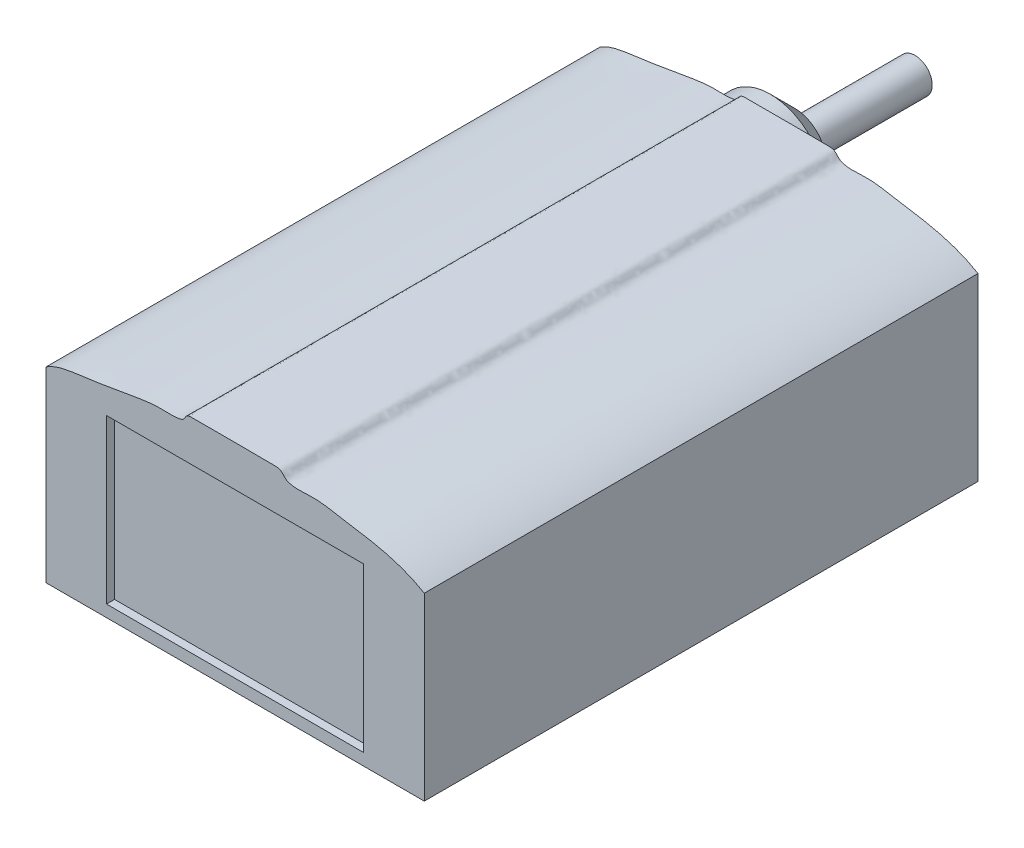
SolidWorks part; units mm, degrees
ref_plane "Спереди" through (0, 0, 0) normal (0, 0, 1) x (1, 0, 0)
ref_plane "Сверху" through (0, 0, 0) normal (0, 1, 0) x (1, 0, 0)
ref_plane "Справа" through (0, 0, 0) normal (1, 0, 0) x (0, 0, -1)
sketch "Эскиз2" plane through (0, 0, 0) normal (0, 0, 1) x (1, 0, 0)
  line L0 (-188.0475, -103.6209) -> (-140.9775, -103.6209) construction
  line L3 (-188.0519, -83.2642) -> (-188.0519, -106.5212)
  line L4 (-188.0519, -106.5212) -> (-140.9819, -106.5212)
  line L5 (-140.9819, -84.1097) -> (-140.9819, -106.5212)
  spline S0 degree 3 poles (-188.0519, -83.2642) (-186.7514, -82.4001) (-184.0147, -82.0982) (-180.2698, -81.5393) (-177.1144, -80.9668) (-174.1299, -80.4879) (-172.3112, -80.7264) (-170.781, -80.4021) (-170.711, -79.668) (-168.6764, -79.5975) (-161.9112, -79.6747) (-158.7559, -79.6611) (-158.3387, -80.4501) (-156.8599, -80.9524) (-154.6505, -80.5007) (-151.0707, -81.2671) (-146.3736, -81.8973) (-142.9268, -82.9516) (-140.9819, -84.1097) knots 0 0 0 0 0.130689 0.231656 0.325449 0.407811 0.483445 0.495515 0.524852 0.540814 0.63917 0.653662 0.671246 0.679565 0.734653 0.804528 0.874807 1 1 1 1
  dimension "D1" = 47.07
  dimension "D2" = 47.07
extrude "Бобышка-Вытянуть1" add sketch "Эскиз2" along normal blind 68.9
sketch "Эскиз3" plane through (0, 0, 0) normal (0, 0, -1) x (-1, 0, 0)
  circle A0 centre (176.6111, -94.4581) radius 6.95
  dimension "D1" = 13.9
extrude "Бобышка-Вытянуть2" add sketch "Эскиз3" along normal blind 12.8
chamfer "Фаска1" distance 3 angle 45 1 edges at (-183.5611, -94.4581, -12.8)
sketch "Эскиз4" plane through (0, 0, -12.8) normal (0, 0, -1) x (-1, 0, 0)
  circle A0 centre (176.6111, -94.4581) radius 2.1358
extrude "Бобышка-Вытянуть3" add sketch "Эскиз4" along normal blind 15
sketch "Эскиз5" plane through (0, 0, 68.9) normal (0, 0, 1) x (1, 0, 0)
  line L0 (-164.5169, -106.5212) -> (-164.5169, -76.1098) construction
  line L1 (-180.5169, -84.7327) -> (-148.5169, -84.7327)
  line L2 (-180.5169, -84.7327) -> (-180.5169, -105.0527)
  line L3 (-180.5169, -105.0527) -> (-148.5169, -105.0527)
  line L4 (-148.5169, -84.7327) -> (-148.5169, -105.0527)
  line L5 (-188.0519, -106.5212) -> (-140.9819, -106.5212) construction
  line L6 (-188.0519, -94.8927) -> (-140.9819, -94.8927) construction
  line L7 (-188.0519, -83.2642) -> (-188.0519, -106.5212) construction
  line L8 (-140.9819, -106.5212) -> (-140.9819, -84.1097) construction
  point P8 (-164.5169, -84.7327)
  point P15 (-180.5169, -94.8927)
  dimension "D1" = 32
  dimension "D2" = 20.32
extrude "Вырез-Вытянуть1" cut sketch "Эскиз5" against normal blind 1
ref_plane "Плоскость4" through (-164.5169, 0, 0) normal (1, 0, 0) x (0, 0, -1)
ref_plane "Плоскость5" through (0, -105.0527, 0) normal (0, 1, 0) x (1, 0, 0)
ref_plane "Плоскость6" through (0, 0, 68.9) normal (0, 0, 1) x (1, 0, 0)
